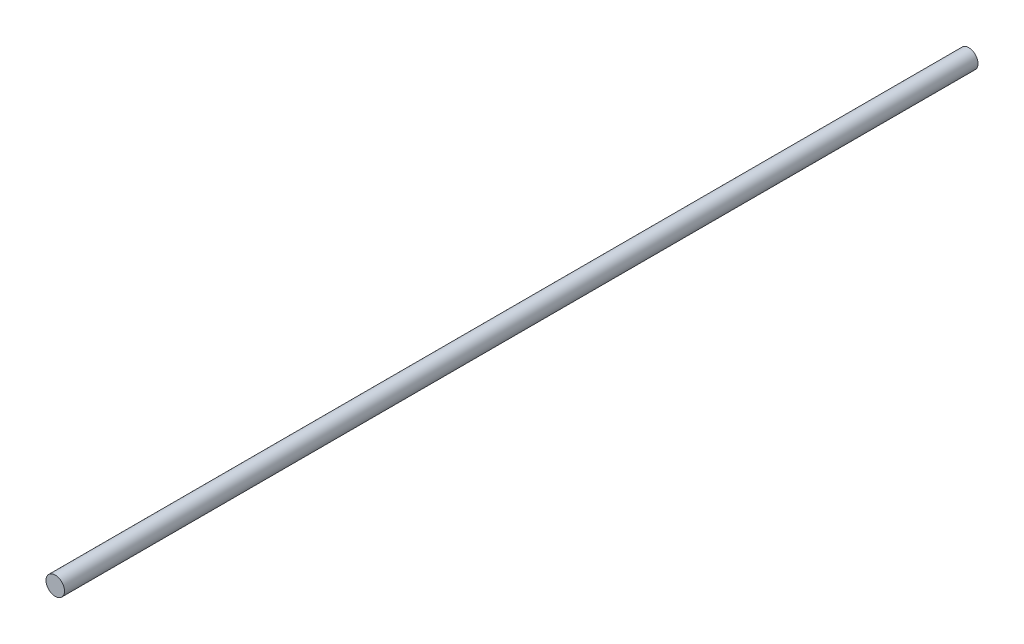
SolidWorks part; units mm, degrees
material "1060 Alloy"
ref_plane "Front Plane" through (0, 0, 0) normal (0, 0, 1) x (1, 0, 0)
ref_plane "Top Plane" through (0, 0, 0) normal (0, 1, 0) x (1, 0, 0)
ref_plane "Right Plane" through (0, 0, 0) normal (1, 0, 0) x (0, 0, -1)
sketch "Sketch1" plane through (0, 0, 0) normal (0, 0, 1) x (1, 0, 0)
  circle A0 centre (0, 0) radius 4
  dimension "D1" = 8
extrude "Boss-Extrude1" add sketch "Sketch1" along normal blind 395
